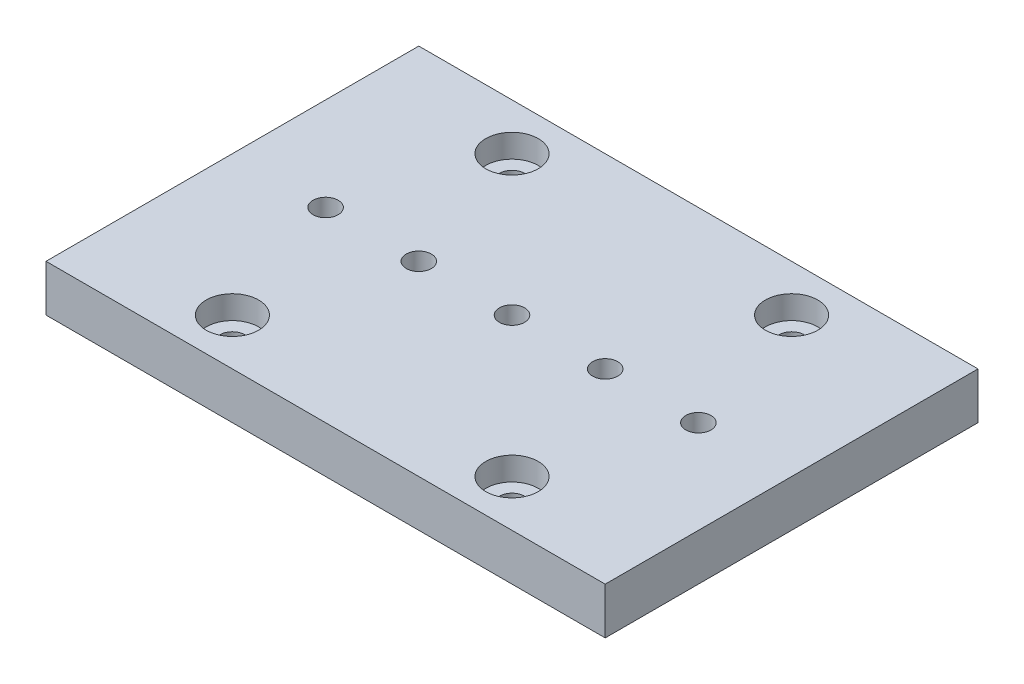
SolidWorks part; units mm, degrees
ref_plane "Front Plane" through (0, 0, 0) normal (0, 0, 1) x (1, 0, 0)
ref_plane "Top Plane" through (0, 0, 0) normal (0, 1, 0) x (1, 0, 0)
ref_plane "Right Plane" through (0, 0, 0) normal (1, 0, 0) x (0, 0, -1)
sketch "Sketch1" plane through (0, 0, 0) normal (0, 1, 0) x (1, 0, 0)
  line L1 (-76.2, -50.8) -> (76.2, -50.8)
  line L2 (-76.2, -50.8) -> (-76.2, 50.8)
  line L3 (-76.2, 50.8) -> (76.2, 50.8)
  line L4 (76.2, -50.8) -> (76.2, 50.8)
  line L5 (-76.2, -50.8) -> (76.2, 50.8) construction
  line L6 (-76.2, 50.8) -> (76.2, -50.8) construction
  point P0 (0, 0)
  dimension "D1" = 152.4
  dimension "D2" = 101.6
extrude "Boss-Extrude1" add sketch "Sketch1" along normal blind 12.7
hole_wizard "CBORE for 1/4 Binding Head Machine Screw1" positions "Sketch2" profile "Sketch3" counterbore size "1/4" standard "ANSI Inch" end condition through all
sketch "Sketch2" plane through (0, 12.7, 0) normal (0, 1, 0) x (1, 0, 0)
  point P0 (-38.1, 38.1)
  point P7 (38.1, 38.1)
  point P8 (38.1, -38.1)
  point P9 (-38.1, -38.1)
  dimension "D1" = 38.1
  dimension "D2" = 38.1
  dimension "D3" = 2
  dimension "D4" = 2
sketch "Sketch3" plane through (-38.1, 12.7, -38.1) normal (1, 0, 0) x (0, 0, 1)
  line L0 (0, 0) -> (0, 12.7)
  line L1 (0, 12.7) -> (3.429, 12.7)
  line L3 (3.429, 12.7) -> (3.429, 6.35)
  line L4 (3.429, 6.35) -> (7.1437, 6.35)
  line L5 (7.1437, 6.35) -> (7.1437, 0)
  line L7 (7.1437, 0) -> (0, 0)
  line L11 (0, -6.35) -> (0, 107.95) construction
  dimension "Thru Hole Dia." = 6.858
  dimension "Thru Hole Depth" = 12.7
  dimension "C'Bore Dia." = 14.2875
  dimension "C'Bore Depth" = 6.35
hole_wizard "1/4 (0.25) Diameter Hole1" positions "Sketch4" profile "Sketch5" hole size "1/4" standard "ANSI Inch" end condition through all
sketch "Sketch4" plane through (0, 12.7, 0) normal (0, 1, 0) x (1, 0, 0)
  point P0 (0, 0)
  point P7 (25.4, 0)
  point P8 (50.8, 0)
  point P11 (-25.4, 0)
  point P12 (-50.8, 0)
  dimension "D1" = 3
  dimension "D2" = 3
sketch "Sketch5" plane through (0, 12.7, 0) normal (1, 0, 0) x (0, 0, 1)
  line L0 (0, 0) -> (0, 12.7)
  line L1 (0, 12.7) -> (3.429, 12.7)
  line L2 (3.429, 12.7) -> (3.429, 0)
  line L5 (3.429, 0) -> (0, 0)
  line L11 (0, -6.35) -> (0, 107.95) construction
  dimension "Thru Hole Dia." = 6.858
  dimension "Thru Hole Depth" = 12.7
sketch "Sketch6" plane through (0, 0, 0) normal (0, -1, 0) x (1, 0, 0)
  line L0 (19.9072, -3.1712) -> (25.4, -6.3425)
  line L1 (50.8, 6.3425) -> (45.3072, 3.1712)
  line L2 (45.3072, 3.1712) -> (45.3072, -3.1712)
  line L3 (45.3072, -3.1712) -> (50.8, -6.3425)
  line L4 (50.8, -6.3425) -> (56.2928, -3.1712)
  line L5 (56.2928, -3.1712) -> (56.2928, 3.1712)
  line L6 (56.2928, 3.1712) -> (50.8, 6.3425)
  line L7 (25.4, -6.3425) -> (30.8928, -3.1712)
  line L8 (30.8928, -3.1712) -> (30.8928, 3.1712)
  line L9 (30.8928, 3.1712) -> (25.4, 6.3425)
  line L10 (19.9072, 3.1712) -> (19.9072, -3.1712)
  line L11 (25.4, 6.3425) -> (19.9072, 3.1712)
  line L12 (-5.4928, -3.1712) -> (0, -6.3425)
  line L13 (0, -6.3425) -> (5.4928, -3.1712)
  line L14 (5.4928, -3.1712) -> (5.4928, 3.1712)
  line L15 (5.4928, 3.1712) -> (0, 6.3425)
  line L16 (-5.4928, 3.1712) -> (-5.4928, -3.1712)
  line L17 (0, 6.3425) -> (-5.4928, 3.1712)
  line L18 (-30.8927, -3.1712) -> (-25.4, -6.3425)
  line L19 (-25.4, -6.3425) -> (-19.9072, -3.1712)
  line L20 (-19.9072, -3.1712) -> (-19.9072, 3.1712)
  line L21 (-19.9072, 3.1712) -> (-25.4, 6.3425)
  line L22 (-30.8927, 3.1712) -> (-30.8927, -3.1712)
  line L23 (-25.4, 6.3425) -> (-30.8927, 3.1712)
  line L24 (-56.2928, -3.1712) -> (-50.8, -6.3425)
  line L25 (-50.8, -6.3425) -> (-45.3072, -3.1712)
  line L26 (-45.3072, -3.1712) -> (-45.3072, 3.1712)
  line L27 (-45.3072, 3.1712) -> (-50.8, 6.3425)
  line L28 (-56.2928, 3.1712) -> (-56.2928, -3.1712)
  line L29 (-50.8, 6.3425) -> (-56.2928, 3.1712)
  circle A0 centre (50.8, 0) radius 5.4927 construction
  dimension "D1" = 10.9855
  dimension "D2" = 5
extrude "Cut-Extrude1" cut sketch "Sketch6" against normal blind 6.35
